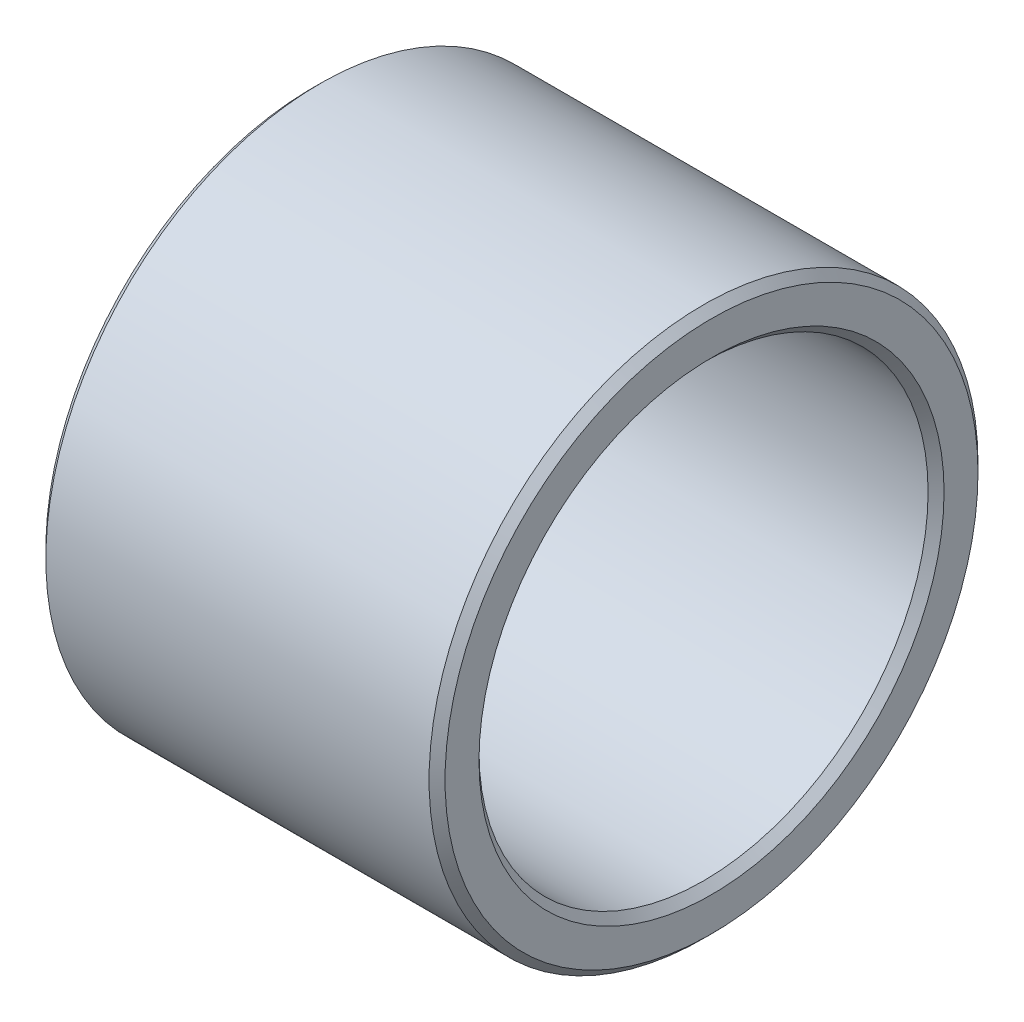
SolidWorks part; units mm, degrees
material "Tin Bearing Bronze"
ref_plane "Front Plane" through (0, 0, 0) normal (0, 0, 1) x (1, 0, 0)
ref_plane "Top Plane" through (0, 0, 0) normal (0, 1, 0) x (1, 0, 0)
ref_plane "Right Plane" through (0, 0, 0) normal (1, 0, 0) x (0, 0, -1)
sketch "Sketch1" plane through (0, 0, 0) normal (1, 0, 0) x (0, 0, -1)
  circle A0 centre (0, 0) radius 14.2875
  circle A1 centre (0, 0) radius 17.4625
  dimension "D1" = 28.575
  dimension "D2" = 34.925
extrude "Boss-Extrude1" add sketch "Sketch1" along normal blind 25.4
chamfer "Chamfer1" distance 0.508 angle 45 4 edges at (25.4, 0, -14.2875) (25.4, 0, -17.4625) (0, 0, -17.4625) (0, 0, -14.2875)
